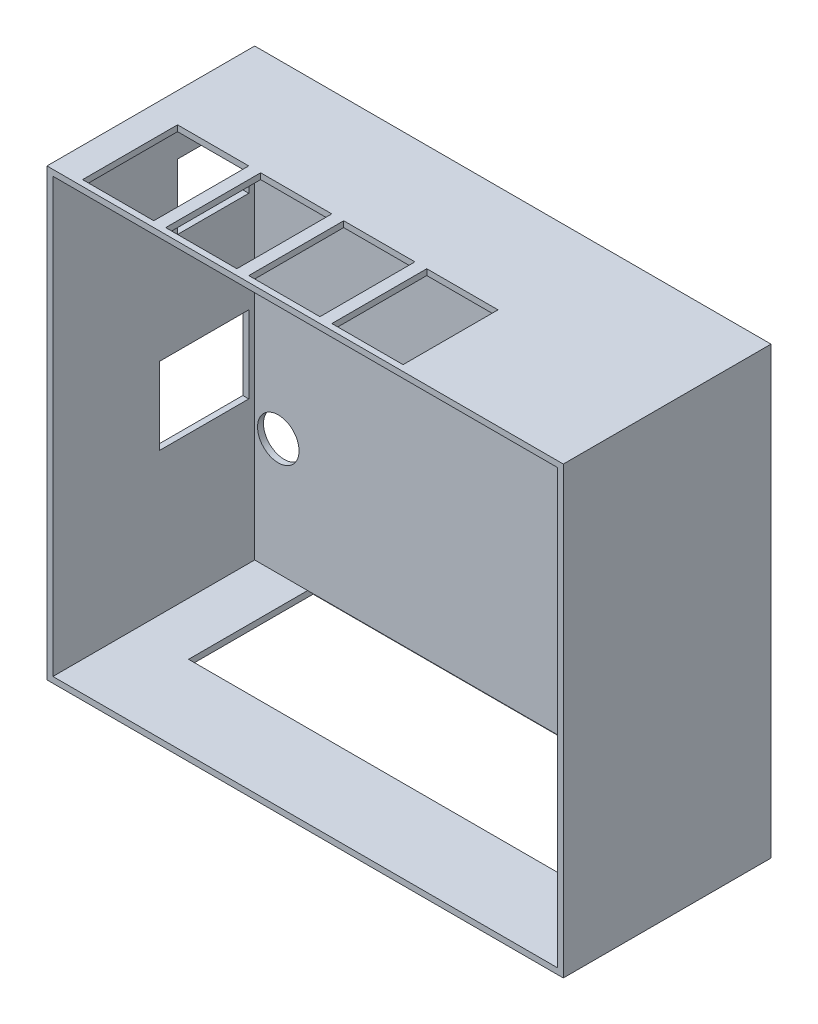
SolidWorks part; units mm, degrees
ref_plane "Plan de face" through (0, 0, 0) normal (0, 0, 1) x (1, 0, 0)
ref_plane "Plan de dessus" through (0, 0, 0) normal (0, 1, 0) x (1, 0, 0)
ref_plane "Plan de droite" through (0, 0, 0) normal (1, 0, 0) x (0, 0, -1)
sketch "Esquisse1" plane through (0, 0, 0) normal (0, 0, 1) x (1, 0, 0)
  line L1 (-132.205, 73) -> (-47.205, 73)
  line L2 (-132.205, 73) -> (-132.205, 0)
  line L3 (-132.205, 0) -> (-47.205, 0)
  line L4 (-47.205, 73) -> (-47.205, 0)
  dimension "D1" = 73
  dimension "D2" = 85
extrude "Boss.-Extru.2" add sketch "Esquisse1" along normal blind 1
sketch "Esquisse6" plane through (-47.205, 0, 0) normal (1, 0, 0) x (0, 0, -1)
  line L1 (0, 73) -> (-35, 73)
  line L2 (0, 73) -> (0, 0)
  line L3 (0, 0) -> (-35, 0)
  line L4 (-35, 73) -> (-35, 0)
  dimension "D1" = 73
  dimension "D2" = 35
extrude "Boss.-Extru.4" add sketch "Esquisse6" along normal blind 1
sketch "Esquisse8" plane through (-132.205, 0, 0) normal (-1, 0, 0) x (0, 0, 1)
  line L1 (0, 73) -> (35, 73)
  line L2 (0, 73) -> (0, 0)
  line L3 (0, 0) -> (35, 0)
  line L4 (35, 73) -> (35, 0)
extrude "Boss.-Extru.6" add sketch "Esquisse8" along normal blind 1
sketch "Esquisse10" plane through (-133.205, 0, 0) normal (-1, 0, 0) x (0, 0, 1)
  line L0 (0, 59.795) -> (2, 59.795) construction
  line L1 (2, 65) -> (14, 65)
  line L2 (2, 65) -> (2, 54)
  line L3 (2, 54) -> (14, 54)
  line L4 (14, 65) -> (14, 54)
  line L5 (0, 73) -> (0, 0) construction
  line L6 (8.5814, 73) -> (8.5814, 65) construction
  line L7 (35, 73) -> (0, 73) construction
  dimension "D1" = 11
  dimension "D2" = 12
extrude "Enlèv. mat.-Extru.1" cut sketch "Esquisse10" against normal blind 1
sketch "Esquisse11" plane through (-133.205, 0, 0) normal (-1, 0, 0) x (0, 0, 1)
  line L0 (11.1338, 0) -> (11.1338, 24) construction
  line L1 (17, 37) -> (2, 37)
  line L2 (17, 37) -> (17, 24)
  line L3 (17, 24) -> (2, 24)
  line L4 (2, 37) -> (2, 24)
  line L5 (0, 0) -> (35, 0) construction
  line L6 (2, 31.8249) -> (0, 31.8249) construction
  line L7 (0, 73) -> (0, 0) construction
  dimension "D1" = 15
  dimension "D2" = 13
extrude "Enlèv. mat.-Extru.2" cut sketch "Esquisse11" against normal blind 1
sketch "Esquisse13" plane through (0, 73, 0) normal (0, 1, 0) x (1, 0, 0)
  line L1 (-133.205, 0) -> (-46.205, 0)
  line L2 (-133.205, 0) -> (-133.205, -35)
  line L3 (-133.205, -35) -> (-46.205, -35)
  line L4 (-46.205, 0) -> (-46.205, -35)
  dimension "D1" = 35
  dimension "D2" = 87
extrude "Boss.-Extru.8" add sketch "Esquisse13" along normal blind 1
sketch "Esquisse14" plane through (0, 74, 0) normal (0, 1, 0) x (1, 0, 0)
  line L0 (-116.2799, -34) -> (-116.2799, -35) construction
  line L1 (-128.207, -18) -> (-116.207, -18)
  line L2 (-128.207, -18) -> (-128.207, -34)
  line L3 (-128.207, -34) -> (-116.207, -34)
  line L4 (-116.207, -18) -> (-116.207, -34)
  line L5 (-133.205, -35) -> (-46.205, -35) construction
  line L6 (-128.207, -21.7805) -> (-133.205, -21.7805) construction
  line L7 (-133.205, 0) -> (-133.205, -35) construction
  line L8 (-122.1939, -35) -> (-122.207, -34)
  line L9 (-123.3121, -18) -> (-123.3121, 0) construction
  line L10 (-46.205, 0) -> (-133.205, 0) construction
  dimension "D1" = 12
  dimension "D2" = 16
extrude "Enlèv. mat.-Extru.3" cut sketch "Esquisse14" against normal blind 1 contours L2 L1 L4 L3
sketch "Esquisse18" plane through (0, 74, 0) normal (0, 1, 0) x (1, 0, 0)
  line L1 (-114.207, -18) -> (-102.207, -18)
  line L2 (-114.207, -18) -> (-114.207, -34)
  line L3 (-114.207, -34) -> (-102.207, -34)
  line L4 (-102.207, -18) -> (-102.207, -34)
  line L6 (-108.207, -18) -> (-108.207, 0) construction
  line L7 (-46.205, 0) -> (-133.205, 0) construction
  line L8 (-116.207, -27.2223) -> (-114.207, -27.2223) construction
  line L9 (-116.207, -18) -> (-116.207, -34) construction
  dimension "D1" = 12
  dimension "D2" = 16
extrude "Enlèv. mat.-Extru.5" cut sketch "Esquisse18" against normal blind 1
sketch "Esquisse20" plane through (0, 74, 0) normal (0, 1, 0) x (1, 0, 0)
  line L0 (-94.6424, 0) -> (-94.6424, -18) construction
  line L1 (-100.207, -18) -> (-88.207, -18)
  line L2 (-100.207, -18) -> (-100.207, -34)
  line L3 (-100.207, -34) -> (-88.207, -34)
  line L4 (-88.207, -18) -> (-88.207, -34)
  line L5 (-46.205, 0) -> (-133.205, 0) construction
  line L6 (-100.207, -27.2382) -> (-102.207, -27.2382) construction
  line L7 (-102.207, -34) -> (-102.207, -18) construction
  dimension "D1" = 12
  dimension "D2" = 16
extrude "Enlèv. mat.-Extru.6" cut sketch "Esquisse20" against normal blind 1
sketch "Esquisse21" plane through (0, 74, 0) normal (0, 1, 0) x (1, 0, 0)
  line L0 (-81.659, 0) -> (-81.659, -18) construction
  line L1 (-86.207, -18) -> (-74.207, -18)
  line L2 (-86.207, -18) -> (-86.207, -34)
  line L3 (-86.207, -34) -> (-74.207, -34)
  line L4 (-74.207, -18) -> (-74.207, -34)
  line L5 (-46.205, 0) -> (-133.205, 0) construction
  line L6 (-86.207, -22.4048) -> (-88.207, -22.4048) construction
  line L7 (-88.207, -34) -> (-88.207, -18) construction
  dimension "D1" = 12
  dimension "D2" = 16
extrude "Enlèv. mat.-Extru.7" cut sketch "Esquisse21" against normal blind 1
sketch "Esquisse22" plane through (0, 0, 1) normal (0, 0, 1) x (1, 0, 0)
  circle A0 centre (-128.3346, 69.1704) radius 3.5
  point P2 (-126.7929, 68.8457)
  point P3 (-127.9568, 68.3608)
  point P4 (-128.3346, 69.1704)
extrude "Enlèv. mat.-Extru.8" cut sketch "Esquisse22" against normal blind 1
sketch "Esquisse23" plane through (0, 0, 1) normal (0, 0, 1) x (1, 0, 0)
  circle A0 centre (-128.2288, 19.6605) radius 3.5
  point P2 (-128.2288, 19.6605)
sketch "Esquisse24" plane through (0, 0, 1) normal (0, 0, 1) x (1, 0, 0)
  line L0 (-73.2164, 68.5259) -> (-74.2164, 68.5259) construction
  circle A0 centre (-69.7164, 68.5259) radius 3.5
  point P2 (-74.2164, 68.5259)
extrude "Enlèv. mat.-Extru.10" cut sketch "Esquisse24" against normal blind 1 contours A0
sketch "Esquisse25" plane through (0, 0, 0) normal (0, -1, 0) x (1, 0, 0)
  line L1 (-133.205, 35) -> (-46.205, 35)
  line L2 (-133.205, 35) -> (-133.205, 0)
  line L3 (-133.205, 0) -> (-46.205, 0)
  line L4 (-46.205, 35) -> (-46.205, 0)
extrude "Boss.-Extru.11" add sketch "Esquisse25" along normal blind 1
sketch "Esquisse26" plane through (0, -1, 0) normal (0, -1, 0) x (1, 0, 0)
  line L1 (-123.286, 21.0671) -> (-46.286, 21.0671)
  line L2 (-123.286, 21.0671) -> (-123.286, 0.0671)
  line L3 (-123.286, 0.0671) -> (-46.286, 0.0671)
  line L4 (-46.286, 21.0671) -> (-46.286, 0.0671)
  dimension "D1" = 77
  dimension "D2" = 21
extrude "Enlèv. mat.-Extru.12" cut sketch "Esquisse23" against normal blind 1
extrude "Enlèv. mat.-Extru.13" cut sketch "Esquisse26" against normal blind 1
